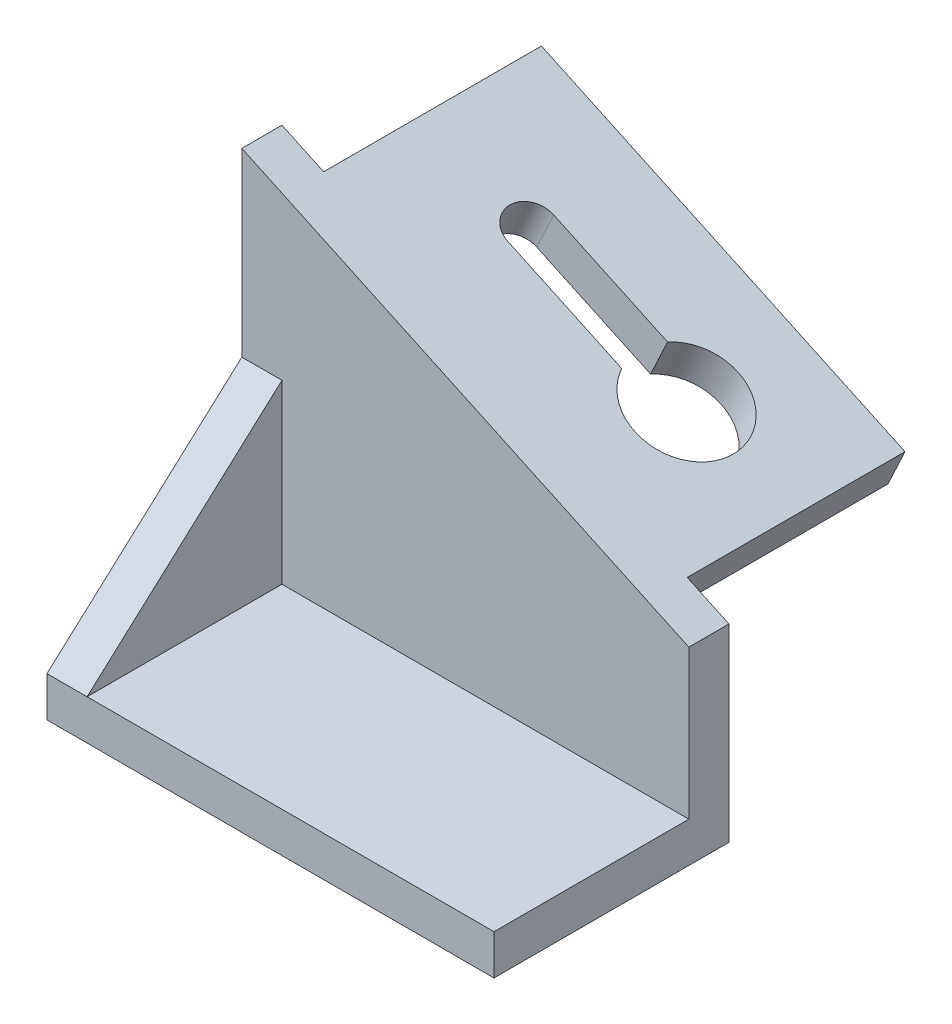
SolidWorks part; units mm, degrees
ref_plane "Front Plane" through (0, 0, 0) normal (0, 0, 1) x (1, 0, 0)
ref_plane "Top Plane" through (0, 0, 0) normal (0, 1, 0) x (1, 0, 0)
ref_plane "Right Plane" through (0, 0, 0) normal (1, 0, 0) x (0, 0, -1)
sketch "Sketch1" plane through (0, 0, 0) normal (0, 1, 0) x (1, 0, 0)
  line L1 (-39, -17) -> (39, -17)
  line L2 (-39, -17) -> (-39, 17)
  line L3 (-39, 17) -> (39, 17)
  line L4 (39, -17) -> (39, 17)
  line L5 (-39, -17) -> (39, 17) construction
  line L6 (-39, 17) -> (39, -17) construction
  point P0 (0, 0)
  dimension "D1" = 34
  dimension "D2" = 78
extrude "Boss-Extrude1" add sketch "Sketch1" along normal blind 7
sketch "Sketch3" plane through (-39, 0, 0) normal (-1, 0, 0) x (0, 0, 1)
  line L0 (17, 7) -> (-17, 37.8196)
  line L1 (-17, 37.8196) -> (-17, 7)
  line L6 (-17, 0) -> (17, 0)
  line L7 (17, 0) -> (17, 7)
  line L8 (17, 7) -> (-17, 7)
  line L9 (-17, 7) -> (-17, 0)
  line L12 (17, 7) -> (-17, 7)
  point P3 (0, 0)
  dimension "D1" = 0
extrude "Boss-Extrude2" add sketch "Sketch3" against normal blind 7
sketch "Sketch4" plane through (0, 0, -17) normal (0, 0, -1) x (-1, 0, 0)
  line L0 (-39, 0) -> (-39, 33)
  line L1 (-39, 33) -> (39, 69.372)
  line L2 (-39, 0) -> (39, 0)
  line L3 (39, 0) -> (39, 69.372)
  point P3 (39, 69.4402)
  dimension "D1" = 33
  dimension "D2" = 25
extrude "Boss-Extrude3" add sketch "Sketch4" along normal blind 7
ref_plane "Plane1" through (19.6054, 42.0439, 0) normal (0.4226, 0.9063, 0) x (0.9063, -0.4226, 0)
sketch "Sketch6" plane through (19.6054, 42.0439, 0) normal (0.4226, 0.9063, 0) x (0.9063, -0.4226, 0)
  line L0 (-64.6639, 24) -> (21.3996, 24) construction
  line L1 (-56.6321, 24) -> (13.3679, 24)
  line L2 (-56.6321, 24) -> (-56.6321, 62)
  line L3 (-56.6321, 62) -> (13.3679, 62)
  line L4 (13.3679, 24) -> (13.3679, 62)
  line L5 (-64.6639, 17) -> (21.3996, 17) construction
  point P9 (-21.6321, 17)
  point P10 (-21.6321, 24)
  dimension "D1" = 45
  dimension "D2" = 70
extrude "Boss-Extrude4" add sketch "Sketch6" against normal blind 7
sketch "Sketch7" plane through (19.6054, 42.0439, 0) normal (0.4226, 0.9063, 0) x (0.9063, -0.4226, 0)
  line L0 (13.3679, 24) -> (13.3679, 62) construction
  line L1 (13.3679, 62) -> (-56.6321, 62) construction
  line L3 (-14.6944, 38) -> (-36.6321, 38)
  line L5 (-14.6944, 46) -> (-36.6321, 46)
  arc A0 (-14.6944, 38) -> (-14.6944, 46) centre (-6.6321, 42) ccw
  arc A1 (-36.6321, 46) -> (-36.6321, 38) centre (-36.6321, 42) ccw
  dimension "D3" = 18
  dimension "D4" = 8
  dimension "D1" = 20
  dimension "D2" = 20
  dimension "D5" = 30
extrude "Cut-Extrude1" cut sketch "Sketch7" against normal blind 7
